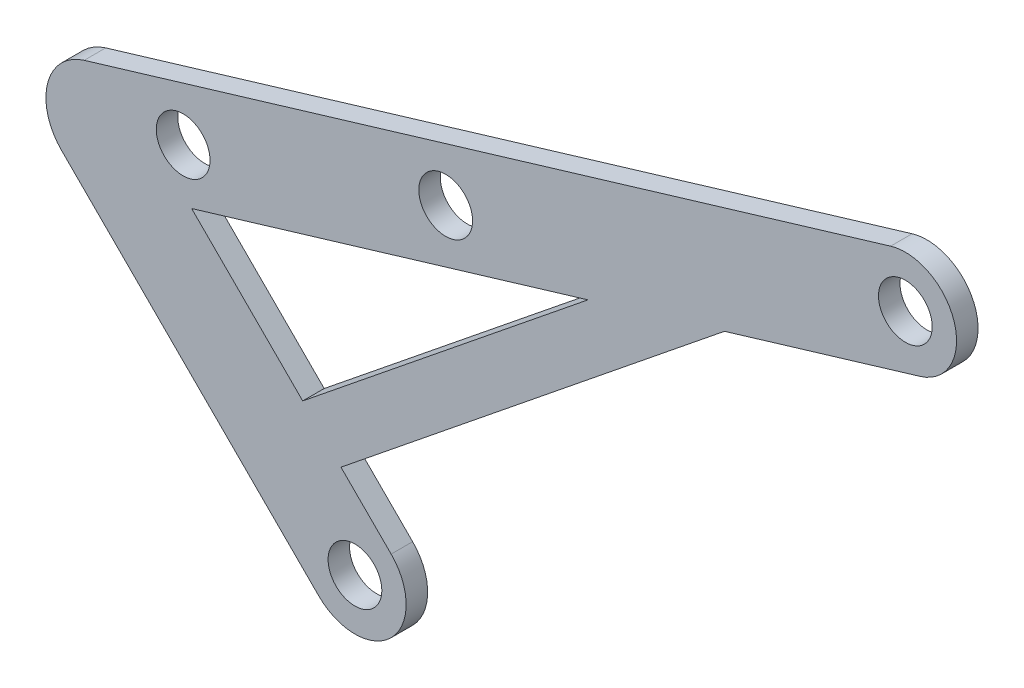
SolidWorks part; units mm, degrees
ref_plane "Front Plane" through (0, 0, 0) normal (0, 0, 1) x (1, 0, 0)
ref_plane "Top Plane" through (0, 0, 0) normal (0, 1, 0) x (1, 0, 0)
ref_plane "Right Plane" through (0, 0, 0) normal (1, 0, 0) x (0, 0, -1)
sketch "Sketch2" plane through (0, 0, 0) normal (0, 0, 1) x (1, 0, 0)
  line L0 (-41.3444, 0) -> (-91.4355, 0) construction
  line L1 (-91.4355, 0) -> (-77.9651, 13.4704) construction
  line L2 (-91.4355, 0) -> (-151.0973, 59.6619) construction
  line L3 (-77.9651, 13.4704) -> (-115.0845, 50.5899) construction
  line L4 (-100.3554, 74.9059) -> (23.9386, 112.2467) construction
  line L5 (-115.0845, 50.5899) -> (13.5223, 89.2263) construction
  line L6 (-100.3554, 74.9059) -> (-167.6048, 54.7027) construction
  line L7 (-77.9651, 13.4704) -> (-115.0845, 50.5899)
  line L8 (13.5223, 89.2263) -> (20.4402, 91.3046) construction
  line L9 (-115.0845, 50.5899) -> (20.4402, 91.3046)
  line L12 (-94.4179, 29.9232) -> (-41.3444, 72.7431)
  line L13 (-87.3002, 22.8055) -> (-15.9478, 80.3728)
  line L14 (-41.3444, 72.7431) -> (-15.9478, 80.3728)
  line L15 (-94.4179, 29.9232) -> (-87.3002, 22.8055)
  line L16 (-41.3444, 72.7431) -> (-35.0238, 64.909) construction
  line L17 (-41.3444, 72.7431) -> (-47.051, 68.139) construction
  line L18 (-94.8743, 56.6615) -> (-100.3554, 74.9059) construction
  line L19 (20.4402, 91.3046) -> (14.9591, 109.5491) construction
  line L20 (14.9591, 109.5491) -> (-151.0973, 59.6619)
  line L21 (-151.0973, 59.6619) -> (-91.4355, 0)
  arc A0 (-77.9651, 13.4704) -> (-91.4355, 0) centre (-84.7003, 6.7352) cw
  circle A3 centre (-84.7003, 6.7352) radius 5
  arc A4 (14.9591, 109.5491) -> (20.4402, 91.3046) centre (17.6996, 100.4268) cw
  circle A5 centre (17.6996, 100.4268) radius 5
  dimension "D12" = 10
  dimension "D2" = 10
  dimension "D1" = 45
  dimension "D4" = 52.4949
  dimension "D6" = 19.05
  dimension "D8" = 61.721
  dimension "D9" = 134.2851
  dimension "D10" = 90
  dimension "D13" = 90
  dimension "D14" = 68.1934
  dimension "D15" = 10.066
  dimension "D16" = 10.066
extrude "Boss-Extrude3" add sketch "Sketch2" along normal blind 4 contours A4 L20 L21 A0 L7 L9 A5 A3 | L7 L13 L9 L12
fillet "Fillet3" radius 10 1 edges at (-151.0973, 59.6619, 2)
sketch "Sketch5" plane through (0, 0, 4) normal (0, 0, 1) x (1, 0, 0)
  line L0 (-119.4039, 69.1833) -> (-113.9228, 50.9389) construction
  line L1 (14.9591, 109.5491) -> (-135.0702, 64.4768) construction
  line L2 (-115.0845, 50.5899) -> (-41.3444, 72.7431) construction
  line L3 (-116.6633, 60.0611) -> (-67.8199, 74.7348) construction
  circle A0 centre (-116.6633, 60.0611) radius 5
  circle A1 centre (-67.8199, 74.7348) radius 5
  dimension "D2" = 10
  dimension "D5" = 10
  dimension "D1" = 90
  dimension "D3" = 90
  dimension "D4" = 51
extrude "Cut-Extrude3" cut sketch "Sketch5" against normal blind 4
